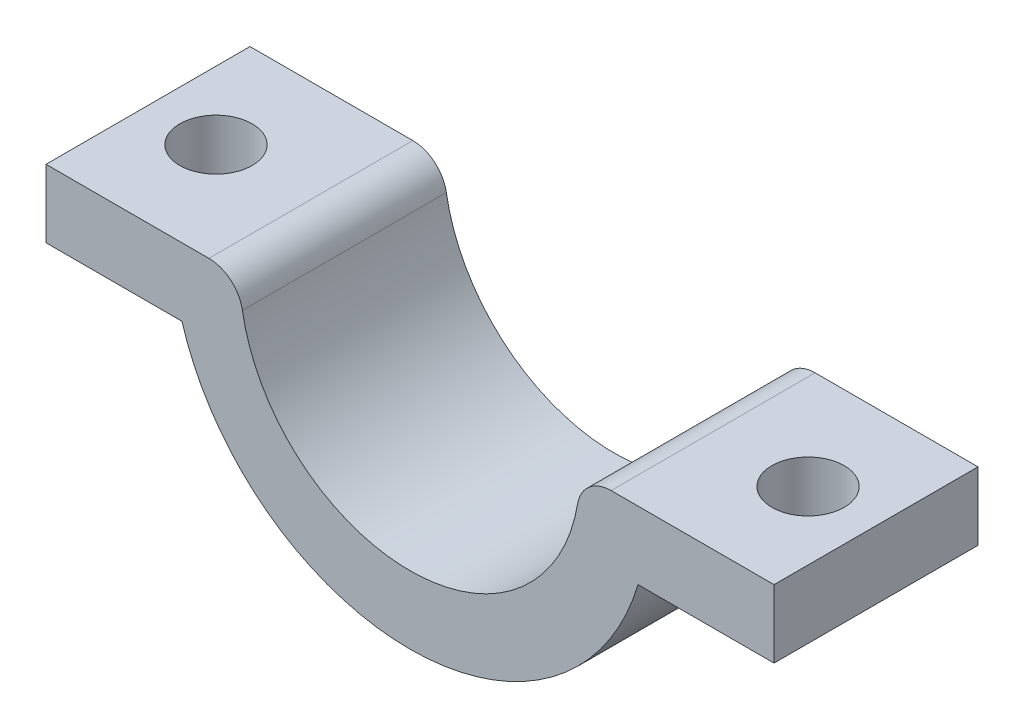
SolidWorks part; units mm, degrees
ref_plane "Front Plane" through (0, 0, 0) normal (0, 0, 1) x (1, 0, 0)
ref_plane "Top Plane" through (0, 0, 0) normal (0, 1, 0) x (1, 0, 0)
ref_plane "Right Plane" through (0, 0, 0) normal (1, 0, 0) x (0, 0, -1)
sketch "Sketch1" plane through (0, 0, 0) normal (0, 0, 1) x (1, 0, 0)
  line L0 (0, -22.225) -> (0, -15.875) construction
  line L1 (-15.875, 0) -> (-33.9985, 0)
  line L2 (-33.9985, 0) -> (-33.9985, -6.35)
  line L3 (-33.9985, -6.35) -> (-21.2985, -6.35)
  line L4 (33.9985, -6.35) -> (21.2985, -6.35)
  line L5 (33.9985, 0) -> (33.9985, -6.35)
  line L6 (15.875, 0) -> (33.9985, 0)
  arc A0 (15.875, 0) -> (-15.875, 0) centre (0, 0) cw
  arc A1 (-21.2985, -6.35) -> (21.2985, -6.35) centre (0, 0) ccw
  point P5 (0.0853, -15.8748)
  point P9 (0, 0)
  point P14 (0, 0)
  point P15 (0, -28.9762)
  point P16 (-20.5097, -6.35)
  point P17 (0, 0)
  dimension "D1" = 6.35
  dimension "D2" = 12.7
  dimension "D3" = 6.35
  dimension "D4" = 15.875
extrude "Boss-Extrude1" add sketch "Sketch1" along normal blind 19.05
sketch "Sketch2" plane through (0, -6.35, 0) normal (0, -1, 0) x (1, 0, 0)
  line L0 (33.9985, 19.05) -> (33.9985, 0) construction
  line L1 (21.2985, 19.05) -> (33.9985, 19.05) construction
  line L2 (-33.9985, 19.05) -> (-33.9985, 0) construction
  line L3 (-33.9985, 19.05) -> (-21.2985, 19.05) construction
  circle A0 centre (27.6485, 9.525) radius 3.3782
  circle A1 centre (-27.6485, 9.525) radius 3.3782
  point P6 (33.9985, 9.525)
  point P9 (27.6485, 19.05)
  point P12 (-33.9985, 9.525)
  point P15 (-27.6485, 19.05)
  dimension "D1" = 6.7564
  dimension "D2" = 6.7564
extrude "Cut-Extrude1" cut sketch "Sketch2" against normal through all
fillet "Fillet1" radius 3.175 2 edges at (-15.875, 0, 9.525) (15.875, 0, 9.525)
